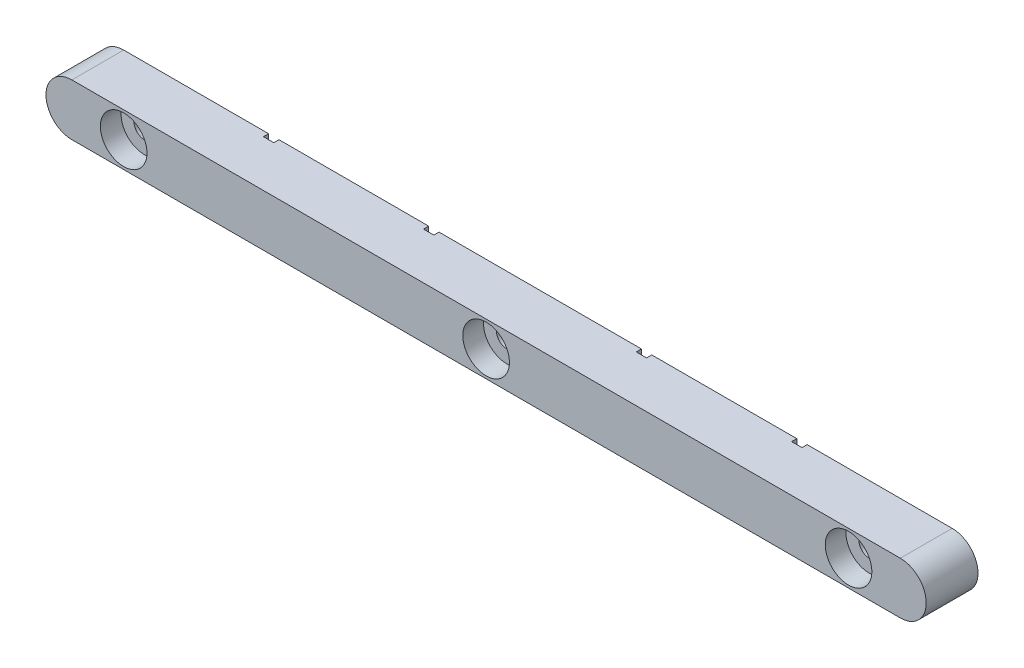
SolidWorks part; units mm, degrees
ref_plane "前视基准面" through (0, 0, 0) normal (0, 0, 1) x (1, 0, 0)
ref_plane "上视基准面" through (0, 0, 0) normal (0, 1, 0) x (1, 0, 0)
ref_plane "右视基准面" through (0, 0, 0) normal (1, 0, 0) x (0, 0, -1)
other "Configuration Table"
sketch "草图1" plane through (0, 0, 0) normal (0, 0, 1) x (1, 0, 0)
  line L0 (0, 0) -> (0, -20669.519) construction
  line L1 (-35, 7.9071) -> (-35, -20661.6118) construction
  line L2 (0, 0) -> (20669.519, 0) construction
  line L3 (35, 9.8393) -> (35, -20659.6797) construction
  line L4 (-40, 2.5) -> (40, 2.5)
  line L5 (-40, -2.5) -> (40, -2.5)
  circle A0 centre (-35, 0) radius 1
  circle A1 centre (0, 0) radius 1
  circle A2 centre (35, 0) radius 1
  arc A3 (-40, 2.5) -> (-40, -2.5) centre (-40, 0) ccw
  arc A4 (40, 2.5) -> (40, -2.5) centre (40, 0) cw
  point P23 (0, 0)
  dimension "D3" = 2
  dimension "D4" = 2
  dimension "D5" = 2
  dimension "D1" = 35
  dimension "D2" = 35
  dimension "D6" = 5
  dimension "D7" = 5
  dimension "D8" = 2.5
  dimension "D9" = 2.5
  dimension "D10" = 5
  dimension "D11" = 5
extrude "凸台-拉伸1" add sketch "草图1" along normal blind 5
sketch "草图2" plane through (0, 0, 0) normal (0, 0, -1) x (-1, 0, 0)
  line L0 (-40, 2.5) -> (40, 2.5) construction
  line L1 (-26, 2.5) -> (-25, 2.5)
  line L2 (-26, 2.5) -> (-26, -2.5)
  line L3 (-26, -2.5) -> (-25, -2.5)
  line L4 (-25, 2.5) -> (-25, -2.5)
  line L5 (40, -2.5) -> (-40, -2.5) construction
  line L7 (-11, 2.5) -> (-10, 2.5)
  line L8 (-11, 2.5) -> (-11, -2.5)
  line L9 (-11, -2.5) -> (-10, -2.5)
  line L10 (-10, 2.5) -> (-10, -2.5)
  line L11 (9.5446, 2.5) -> (10.5446, 2.5)
  line L12 (9.5446, 2.5) -> (9.5446, -2.5)
  line L13 (9.5446, -2.5) -> (10.5446, -2.5)
  line L14 (10.5446, 2.5) -> (10.5446, -2.5)
  line L15 (25, 2.5) -> (26, 2.5)
  line L16 (25, 2.5) -> (25, -2.5)
  line L17 (25, -2.5) -> (26, -2.5)
  line L18 (26, 2.5) -> (26, -2.5)
  dimension "D1" = 25
  dimension "D2" = 1
  dimension "D3" = 1
  dimension "D4" = 10
  dimension "D5" = 9.5446
  dimension "D6" = 1
  dimension "D7" = 25
  dimension "D8" = 1
extrude "切除-拉伸1" cut sketch "草图2" against normal blind 0.5
sketch "草图3" plane through (0, 0, 5) normal (0, 0, 1) x (1, 0, 0)
  circle A0 centre (-35, 0) radius 2.25
  circle A1 centre (0, 0) radius 2.25
  circle A2 centre (35, 0) radius 2.25
  dimension "D1" = 4.5
  dimension "D2" = 4.5
  dimension "D3" = 4.5
extrude "切除-拉伸3" cut sketch "草图3" against normal blind 2
